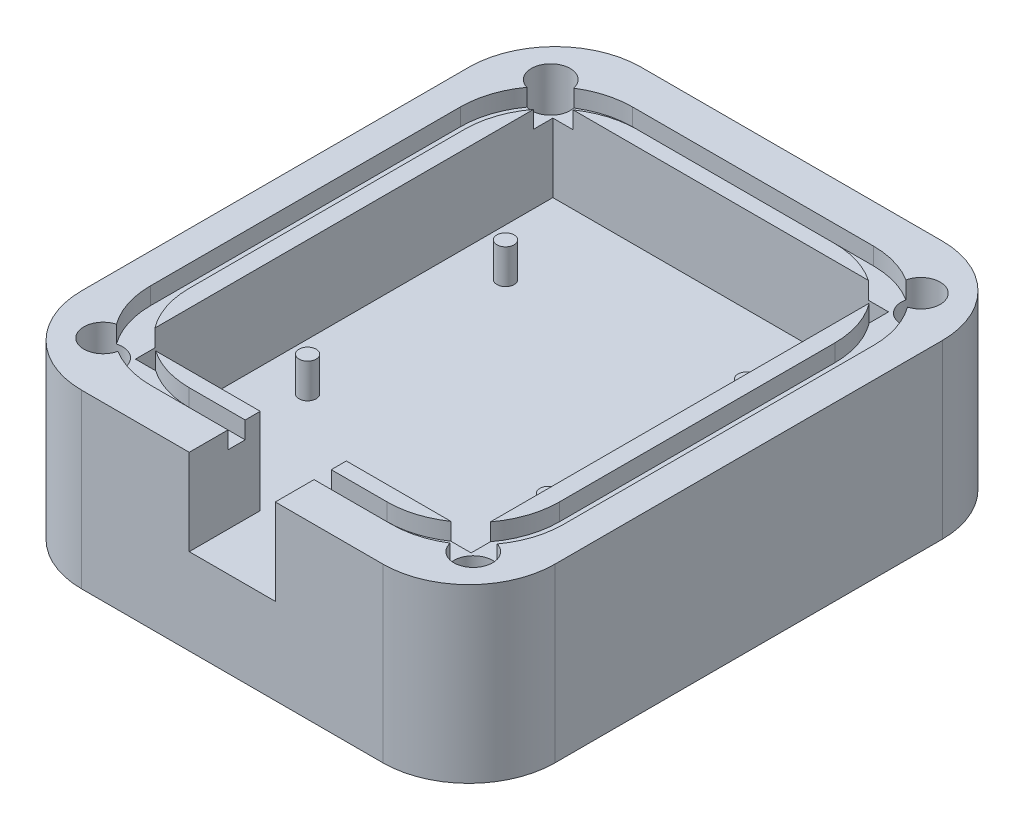
SolidWorks part; units mm, degrees
ref_plane "Front Plane" through (0, 0, 0) normal (0, 0, 1) x (1, 0, 0)
ref_plane "Top Plane" through (0, 0, 0) normal (0, 1, 0) x (1, 0, 0)
ref_plane "Right Plane" through (0, 0, 0) normal (1, 0, 0) x (0, 0, -1)
sketch "Sketch1" plane through (0, 0, 0) normal (0, 1, 0) x (1, 0, 0)
  line L1 (-17.5, 32.5) -> (17.5, 32.5)
  line L2 (-27.5, 22.5) -> (-27.5, -22.5)
  line L3 (-17.5, -32.5) -> (17.5, -32.5)
  line L4 (27.5, 22.5) -> (27.5, -22.5)
  arc A0 (-27.5, -22.5) -> (-17.5, -32.5) centre (-17.5, -22.5) ccw
  arc A1 (17.5, -32.5) -> (27.5, -22.5) centre (17.5, -22.5) ccw
  arc A2 (17.5, 32.5) -> (27.5, 22.5) centre (17.5, 22.5) cw
  arc A3 (-17.5, 32.5) -> (-27.5, 22.5) centre (-17.5, 22.5) ccw
  point P4 (-27.5, 0)
  point P6 (0, 32.5)
  point P9 (-27.5, -32.5)
  point P14 (27.5, 32.5)
  point P17 (-27.5, 32.5)
  dimension "D3" = 10
  dimension "D1" = 55
  dimension "D2" = 65
extrude "Boss-Extrude1" add sketch "Sketch1" along normal blind 10 contours L4 A1 L3 A0 L2 A3 L1 A2
sketch "Sketch2" plane through (0, 10, 0) normal (0, 1, 0) x (1, 0, 0)
  line L0 (27.5, 22.5) -> (27.5, -22.5) construction
  line L1 (-19.5, 24.25) -> (19.5, 24.25)
  line L2 (-19.5, 24.25) -> (-19.5, -24.25)
  line L3 (-19.5, -24.25) -> (19.5, -24.25)
  line L4 (19.5, 24.25) -> (19.5, -24.25)
  line L5 (-17.5, -32.5) -> (17.5, -32.5) construction
  line L6 (-27.5, 22.5) -> (-27.5, -22.5) construction
  line L7 (-17.5, 32.5) -> (17.5, 32.5) construction
  line L8 (27.5, 22.5) -> (27.5, -22.5)
  line L9 (-17.5, -32.5) -> (17.5, -32.5)
  line L10 (-27.5, 22.5) -> (-27.5, -22.5)
  line L11 (-17.5, 32.5) -> (17.5, 32.5)
  arc A0 (27.5, 22.5) -> (17.5, 32.5) centre (17.5, 22.5) ccw construction
  arc A1 (17.5, -32.5) -> (27.5, -22.5) centre (17.5, -22.5) ccw construction
  arc A2 (-27.5, -22.5) -> (-17.5, -32.5) centre (-17.5, -22.5) ccw construction
  arc A3 (-17.5, 32.5) -> (-27.5, 22.5) centre (-17.5, 22.5) ccw construction
  arc A4 (27.5, 22.5) -> (17.5, 32.5) centre (17.5, 22.5) ccw
  arc A5 (17.5, -32.5) -> (27.5, -22.5) centre (17.5, -22.5) ccw
  arc A6 (-27.5, -22.5) -> (-17.5, -32.5) centre (-17.5, -22.5) ccw
  arc A7 (-17.5, 32.5) -> (-27.5, 22.5) centre (-17.5, 22.5) ccw
  point P4 (0, 24.25)
  point P6 (-19.5, 0)
  point P7 (0, 0)
  dimension "D1" = 39
  dimension "D2" = 48.5
extrude "Boss-Extrude2" add sketch "Sketch2" along normal blind 10
sketch "Sketch6" plane through (0, 10, 0) normal (0, 1, 0) x (1, 0, 0)
  line L0 (-14, 13.25) -> (-14, -9.75) construction
  line L1 (-14, 13.25) -> (14, 13.25) construction
  line L2 (-17, 21.75) -> (17, 21.75) construction
  line L3 (17, 21.75) -> (17, -21.75) construction
  line L4 (17, -21.75) -> (-17, -21.75) construction
  line L5 (-17, -21.75) -> (-17, 21.75) construction
  circle A0 centre (-14, 13.25) radius 1
  circle A1 centre (14, 13.25) radius 1
  circle A2 centre (14, -9.75) radius 1
  circle A3 centre (-14, -9.75) radius 1
  point P9 (0, 13.25)
  point P11 (-17, 0)
  point P15 (0, 21.75)
  dimension "D3" = 2
  dimension "D4" = 2
  dimension "D5" = 2
  dimension "D6" = 2
  dimension "D1" = 28
  dimension "D2" = 23
  dimension "D7" = 34
  dimension "D8" = 43.5
  dimension "D9" = 8.5
  dimension "D10" = 3
extrude "Boss-Extrude3" add sketch "Sketch6" along normal blind 4
sketch "Sketch7" plane through (0, 20, 0) normal (0, 1, 0) x (1, 0, 0)
  line L0 (-19.5, -24.25) -> (19.5, -24.25) construction
  line L1 (-5, -24.25) -> (5, -24.25)
  line L2 (-5, -24.25) -> (-5, -32.5)
  line L3 (-5, -32.5) -> (5, -32.5)
  line L4 (5, -24.25) -> (5, -32.5)
  line L5 (-17.5, -32.5) -> (17.5, -32.5) construction
  point P8 (0, -24.25)
  dimension "D1" = 10
extrude "Cut-Extrude1" cut sketch "Sketch7" against normal blind 10
sketch "Sketch8" plane through (0, 20, 0) normal (0, 1, 0) x (1, 0, 0)
  line L0 (-21.5, -26) -> (-21.5, 26) construction
  line L1 (-21.5, 26) -> (21.5, 26) construction
  circle A0 centre (-21.5, -26) radius 2.25
  circle A1 centre (21.5, -26) radius 2.25
  circle A2 centre (21.5, 26) radius 2.25
  circle A3 centre (-21.5, 26) radius 2.25
  point P8 (0, 26)
  point P9 (-21.5, 0)
  dimension "D1" = 4.5
  dimension "D2" = 4.5
  dimension "D3" = 4.5
  dimension "D4" = 4.5
  dimension "D5" = 52
  dimension "D6" = 43
extrude "Cut-Extrude2" cut sketch "Sketch8" against normal blind 15
sketch "Sketch9" plane through (0, 20, 0) normal (0, 1, 0) x (1, 0, 0)
  line L1 (-14, 28) -> (14, 28)
  line L2 (-24, 18) -> (-24, -18)
  line L3 (-14, -28) -> (14, -28)
  line L4 (24, 18) -> (24, -18)
  line L5 (-11.5, 26) -> (11.5, 26)
  line L6 (-21.5, 16) -> (-21.5, -16)
  line L7 (-11.5, -26) -> (11.5, -26)
  line L8 (21.5, 16) -> (21.5, -16)
  arc A0 (11.5, -26) -> (21.5, -16) centre (11.5, -16) ccw
  arc A1 (11.5, 26) -> (21.5, 16) centre (11.5, 16) cw
  arc A2 (-11.5, 26) -> (-21.5, 16) centre (-11.5, 16) ccw
  arc A3 (-21.5, -16) -> (-11.5, -26) centre (-11.5, -16) ccw
  arc A4 (14, -28) -> (19.3016, -26.479) centre (14, -18) ccw
  arc A5 (-24, -18) -> (-22.1197, -23.837) centre (-14, -18) ccw
  arc A6 (14, 28) -> (19.3016, 26.479) centre (14, 18) cw
  arc A7 (-14, 28) -> (-19.3016, 26.479) centre (-14, 18) ccw
  circle A8 centre (-21.5, -26) radius 2.25 construction
  circle A9 centre (21.5, -26) radius 2.25 construction
  circle A10 centre (21.5, 26) radius 2.25 construction
  circle A11 centre (-21.5, 26) radius 2.25 construction
  arc A12 (-19.3016, -26.479) -> (-22.1197, -23.837) centre (-21.5, -26) ccw
  arc A13 (22.1197, -23.837) -> (19.3016, -26.479) centre (21.5, -26) ccw
  arc A14 (19.3016, 26.479) -> (22.1197, 23.837) centre (21.5, 26) ccw
  arc A15 (-22.1197, 23.837) -> (-19.3016, 26.479) centre (-21.5, 26) ccw
  arc A16 (-22.1197, 23.837) -> (-24, 18) centre (-14, 18) ccw
  arc A17 (22.1197, 23.837) -> (24, 18) centre (14, 18) cw
  arc A18 (22.1197, -23.837) -> (24, -18) centre (14, -18) ccw
  arc A19 (-19.3016, -26.479) -> (-14, -28) centre (-14, -18) ccw
  point P4 (0, 28)
  point P6 (-24, 0)
  point P15 (21.5, -26)
  point P20 (-21.5, 26)
  point P27 (-24, -28)
  point P30 (24, 28)
  point P33 (-24, 28)
  dimension "D3" = 10
  dimension "D1" = 48
  dimension "D2" = 56
extrude "Cut-Extrude3" cut sketch "Sketch9" against normal blind 2
